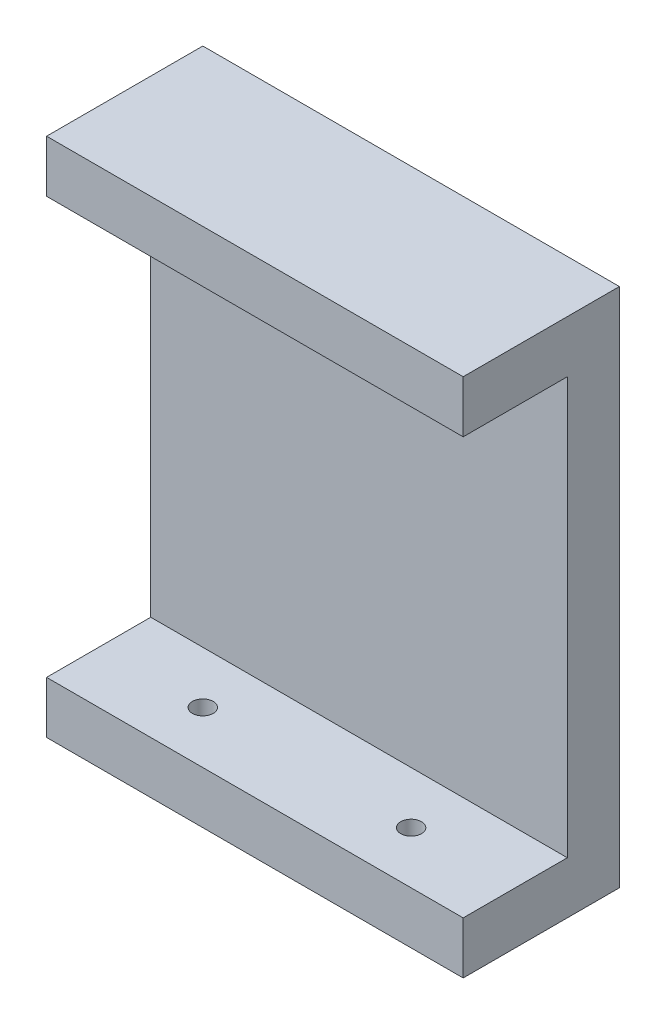
SolidWorks part; units mm, degrees
ref_plane "Front Plane" through (0, 0, 0) normal (0, 0, 1) x (1, 0, 0)
ref_plane "Top Plane" through (0, 0, 0) normal (0, 1, 0) x (1, 0, 0)
ref_plane "Right Plane" through (0, 0, 0) normal (1, 0, 0) x (0, 0, -1)
sketch "Sketch1" plane through (0, 0, 0) normal (0, 0, 1) x (1, 0, 0)
  line L1 (-40, 50) -> (40, 50)
  line L2 (-40, 50) -> (-40, -50)
  line L3 (-40, -50) -> (40, -50)
  line L4 (40, 50) -> (40, -50)
  line L5 (-40, 50) -> (40, -50) construction
  line L6 (-40, -50) -> (40, 50) construction
  point P0 (0, 0)
  dimension "D1" = 80
  dimension "D2" = 100
extrude "Boss-Extrude1" add sketch "Sketch1" along normal blind 10
sketch "Sketch2" plane through (0, 0, 0) normal (0, 0, -1) x (-1, 0, 0)
  line L0 (0, -50) -> (0, 50) construction
  line L1 (40, -50) -> (-40, -50) construction
  line L2 (-40, 50) -> (40, 50) construction
  circle A0 centre (-30, -20) radius 4
  circle A1 centre (30, -20) radius 4
  dimension "D1" = 8
  dimension "D2" = 60
  dimension "D3" = 30
extrude "Cut-Extrude1" cut sketch "Sketch2" against normal blind 7
sketch "Sketch3" plane through (0, 0, 10) normal (0, 0, 1) x (1, 0, 0)
  line L0 (40, -50) -> (40, 50) construction
  line L1 (-40, -50) -> (40, -50)
  line L2 (-40, -50) -> (-40, -40)
  line L3 (-40, -40) -> (40, -40)
  line L4 (40, -50) -> (40, -40)
  line L6 (-40, 50) -> (40, 50)
  line L7 (-40, 50) -> (-40, 40)
  line L8 (-40, 40) -> (40, 40)
  line L9 (40, 50) -> (40, 40)
  dimension "D1" = 10
  dimension "D2" = 10
extrude "Boss-Extrude2" add sketch "Sketch3" along normal blind 20
sketch "Sketch4" plane through (0, -40, 0) normal (0, 1, 0) x (1, 0, 0)
  line L0 (-40, -20) -> (40, -20) construction
  line L3 (0, 0) -> (0, -30) construction
  line L4 (40, 0) -> (-40, 0) construction
  line L5 (40, -30) -> (-40, -30) construction
  line L6 (-40, -30) -> (-40, -10) construction
  line L7 (40, -30) -> (40, -10) construction
  circle A0 centre (-20, -20) radius 2
  circle A1 centre (20, -20) radius 2
  dimension "D1" = 4
  dimension "D2" = 40
extrude "Cut-Extrude2" cut sketch "Sketch4" against normal blind 5 and the other way offset from surface (85 mm away) 5 other way up to face at (0, 40, 20)
